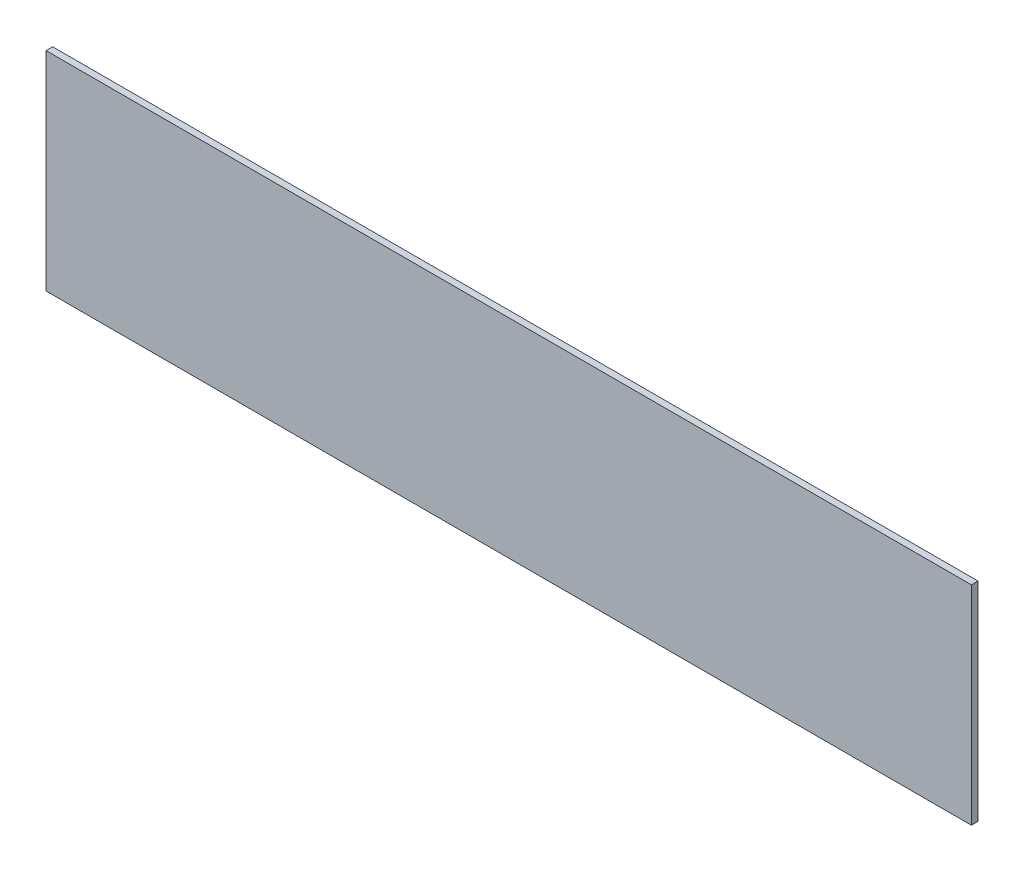
SolidWorks part; units mm, degrees
ref_plane "Front Plane" through (0, 0, 0) normal (0, 0, 1) x (1, 0, 0)
ref_plane "Top Plane" through (0, 0, 0) normal (0, 1, 0) x (1, 0, 0)
ref_plane "Right Plane" through (0, 0, 0) normal (1, 0, 0) x (0, 0, -1)
sketch "Sketch1" plane through (0, 0, 0) normal (0, 0, 1) x (1, 0, 0)
  line L1 (-388.9057, 66.4525) -> (55.5943, 66.4525)
  line L2 (-388.9057, 66.4525) -> (-388.9057, -33.56)
  line L3 (-388.9057, -33.56) -> (55.5943, -33.56)
  line L4 (55.5943, 66.4525) -> (55.5943, -33.56)
  dimension "D1" = 100.0125
  dimension "D2" = 444.5
extrude "Boss-Extrude1" add sketch "Sketch1" against normal blind 3.175
